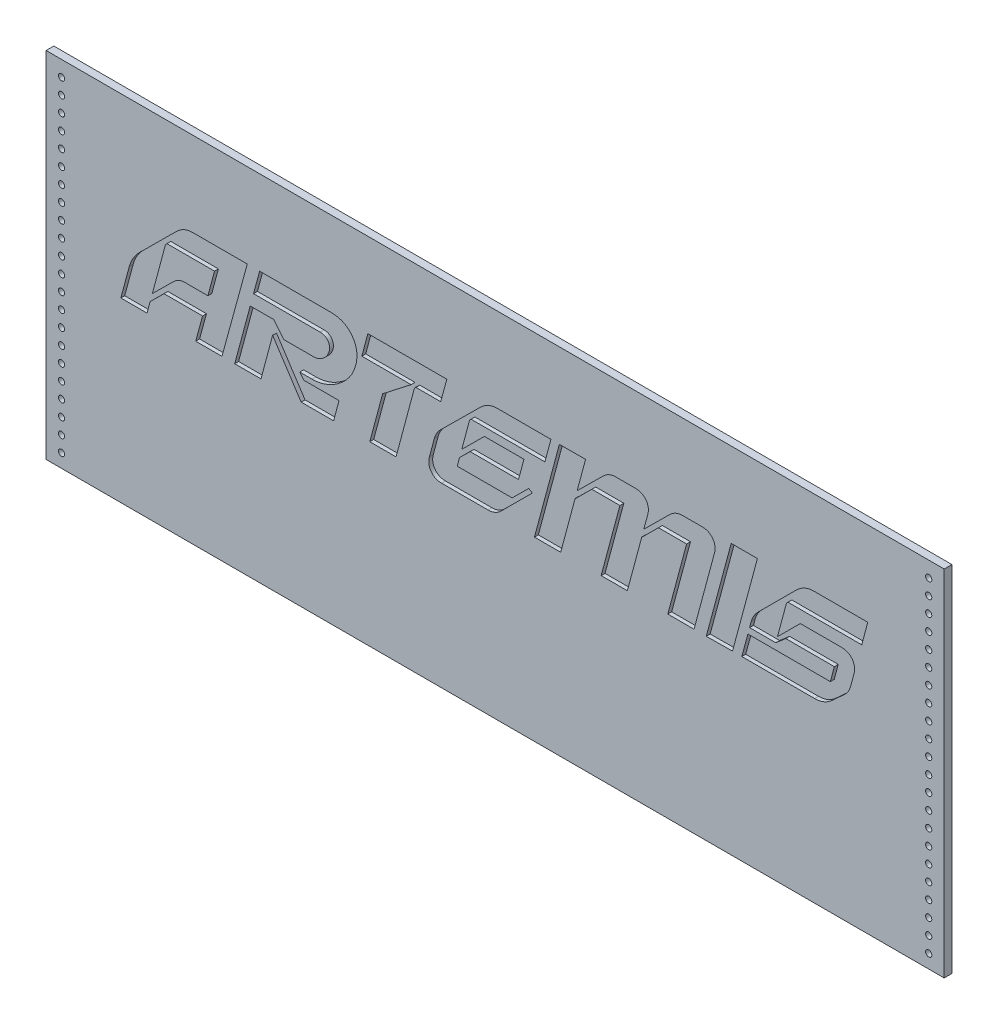
SolidWorks part; units mm, degrees
material "ABS PC"
ref_plane "Front Plane" through (0, 0, 0) normal (0, 0, 1) x (1, 0, 0)
ref_plane "Top Plane" through (0, 0, 0) normal (0, 1, 0) x (1, 0, 0)
ref_plane "Right Plane" through (0, 0, 0) normal (1, 0, 0) x (0, 0, -1)
sketch "Sketch1" plane through (0, 0, 0) normal (0, 0, 1) x (1, 0, 0)
  line L0 (12.7, 0) -> (12.7, -290.5125) construction
  line L1 (0, 0) -> (736.6, 0)
  line L2 (0, 0) -> (0, -290.5125)
  line L3 (0, -290.5125) -> (736.6, -290.5125)
  line L4 (736.6, 0) -> (736.6, -290.5125)
  line L5 (368.3, 0) -> (368.3, -290.5125) construction
  circle A0 centre (12.7, -12.7) radius 2.54
  circle A1 centre (12.7, -25.4) radius 2.54
  circle A2 centre (12.7, -38.1) radius 2.54
  circle A3 centre (12.7, -50.8) radius 2.54
  circle A4 centre (12.7, -63.5) radius 2.54
  circle A5 centre (12.7, -76.2) radius 2.54
  circle A6 centre (12.7, -88.9) radius 2.54
  circle A7 centre (12.7, -101.6) radius 2.54
  circle A8 centre (12.7, -114.3) radius 2.54
  circle A9 centre (12.7, -127) radius 2.54
  circle A10 centre (12.7, -139.7) radius 2.54
  circle A11 centre (12.7, -152.4) radius 2.54
  circle A12 centre (12.7, -165.1) radius 2.54
  circle A13 centre (12.7, -177.8) radius 2.54
  circle A14 centre (12.7, -190.5) radius 2.54
  circle A15 centre (12.7, -203.2) radius 2.54
  circle A16 centre (12.7, -215.9) radius 2.54
  circle A17 centre (12.7, -228.6) radius 2.54
  circle A18 centre (12.7, -241.3) radius 2.54
  circle A19 centre (12.7, -254) radius 2.54
  circle A20 centre (12.7, -266.7) radius 2.54
  circle A21 centre (12.7, -279.4) radius 2.54
  circle A22 centre (723.9, -279.4) radius 2.54
  circle A23 centre (723.9, -266.7) radius 2.54
  circle A24 centre (723.9, -254) radius 2.54
  circle A25 centre (723.9, -241.3) radius 2.54
  circle A26 centre (723.9, -228.6) radius 2.54
  circle A27 centre (723.9, -215.9) radius 2.54
  circle A28 centre (723.9, -203.2) radius 2.54
  circle A29 centre (723.9, -190.5) radius 2.54
  circle A30 centre (723.9, -177.8) radius 2.54
  circle A31 centre (723.9, -165.1) radius 2.54
  circle A32 centre (723.9, -152.4) radius 2.54
  circle A33 centre (723.9, -139.7) radius 2.54
  circle A34 centre (723.9, -127) radius 2.54
  circle A35 centre (723.9, -114.3) radius 2.54
  circle A36 centre (723.9, -101.6) radius 2.54
  circle A37 centre (723.9, -88.9) radius 2.54
  circle A38 centre (723.9, -76.2) radius 2.54
  circle A39 centre (723.9, -63.5) radius 2.54
  circle A40 centre (723.9, -12.7) radius 2.54
  circle A41 centre (723.9, -50.8) radius 2.54
  circle A42 centre (723.9, -38.1) radius 2.54
  circle A43 centre (723.9, -25.4) radius 2.54
  dimension "D4" = 5.08
  dimension "D1" = 290.5125
  dimension "D2" = 736.6
  dimension "D3" = 12.7
  dimension "D5" = 12.7
  dimension "D6" = 22
extrude "Boss-Extrude1" add sketch "Sketch1" along normal blind 6.35
sketch "Sketch2" plane through (0, 0, 6.35) normal (0, 0, 1) x (1, 0, 0)
  line L0 (0, -145.2562) -> (736.6, -145.2562) construction
  line L3 (736.6, -290.5125) -> (736.6, 0) construction
  text T0 "Artemis" font "Sterion" height 76.2
  point P3 (0, -145.2562)
extrude "Cut-Extrude1" cut sketch "Sketch2" against normal blind 3.175
